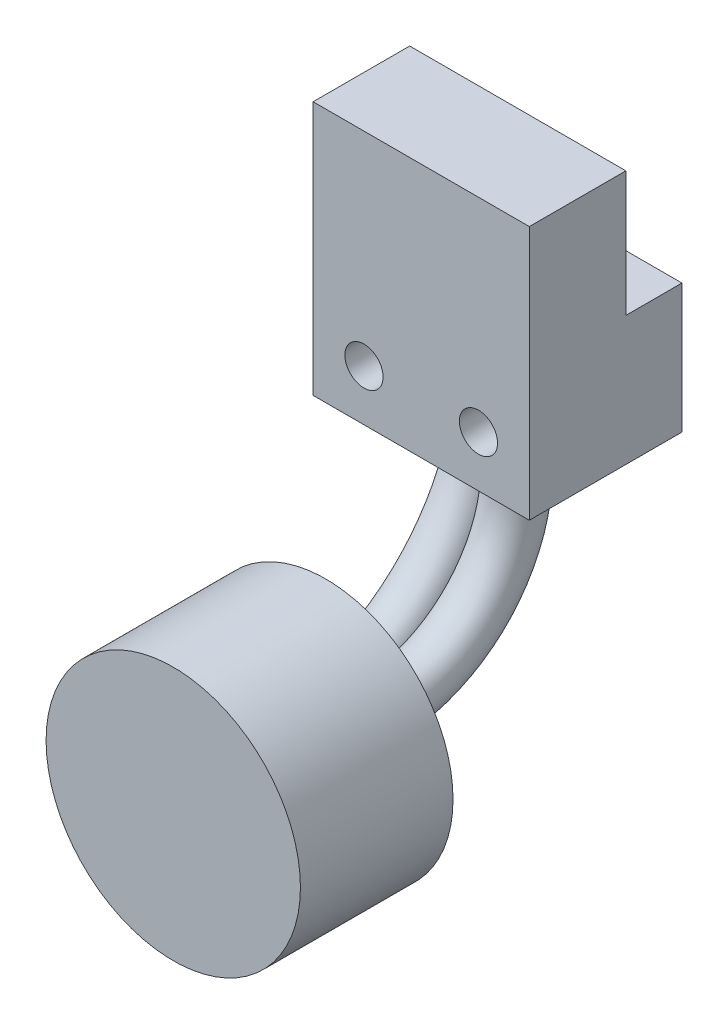
SolidWorks part; units mm, degrees
ref_plane "Přední rovina" through (0, 0, 0) normal (0, 0, 1) x (1, 0, 0)
ref_plane "Horní rovina" through (0, 0, 0) normal (0, 1, 0) x (1, 0, 0)
ref_plane "Pravá rovina" through (0, 0, 0) normal (1, 0, 0) x (0, 0, -1)
sketch "Skica1" plane through (0, 0, 0) normal (0, 0, 1) x (1, 0, 0)
  circle A0 centre (0, 0) radius 50
  dimension "D1" = 100
extrude "Přidat vysunutím1" add sketch "Skica1" along normal blind 60
sketch "Skica2" plane through (0, 0, 0) normal (0, 0, -1) x (-1, 0, 0)
  line L0 (92.8097, 70) -> (-45.2352, 70) construction
  circle A0 centre (20, -15) radius 10
  circle A1 centre (-20, 15) radius 10
  dimension "D1" = 20
  dimension "D2" = 20
  dimension "D6" = 15
  dimension "D3" = 20
  dimension "D4" = 15
  dimension "D5" = 20
  dimension "D7" = 70
revolve "Rotovat1" add sketch "Skica2" angle 90 about L0
sketch "Skica3" plane through (0, 70, 0) normal (0, 1, 0) x (1, 0, 0)
  line L1 (40, 40) -> (-45, 40)
  line L2 (40, 40) -> (40, 100)
  line L3 (40, 100) -> (-45, 100)
  line L4 (-45, 40) -> (-45, 100)
  circle A0 centre (20, 55) radius 10 construction
  dimension "D3" = 15
  dimension "D4" = 20
  dimension "D1" = 60
  dimension "D2" = 85
extrude "Přidat vysunutím2" add sketch "Skica3" along normal blind 100
sketch "Skica4" plane through (-45, 0, 0) normal (-1, 0, 0) x (0, 0, 1)
  line L1 (-77.9588, 173.6668) -> (-104.5936, 173.6668)
  line L2 (-77.9588, 173.6668) -> (-77.9588, 120.7724)
  line L3 (-77.9588, 120.7724) -> (-104.5936, 120.7724)
  line L4 (-104.5936, 173.6668) -> (-104.5936, 120.7724)
extrude "Odebrat vysunutím2" cut sketch "Skica4" against normal blind 100
sketch "Skica5" plane through (0, 0, -40) normal (0, 0, 1) x (1, 0, 0)
  line L0 (40, 170) -> (40, 70) construction
  line L1 (-45, 170) -> (-45, 70) construction
  line L2 (-45, 70) -> (40, 70) construction
  circle A0 centre (20, 90) radius 7.5
  circle A1 centre (-25, 90) radius 7.5
  dimension "D1" = 15
  dimension "D2" = 15
  dimension "D3" = 20
  dimension "D4" = 20
  dimension "D5" = 20
  dimension "D6" = 20
extrude "Odebrat vysunutím3" cut sketch "Skica5" against normal blind 100
